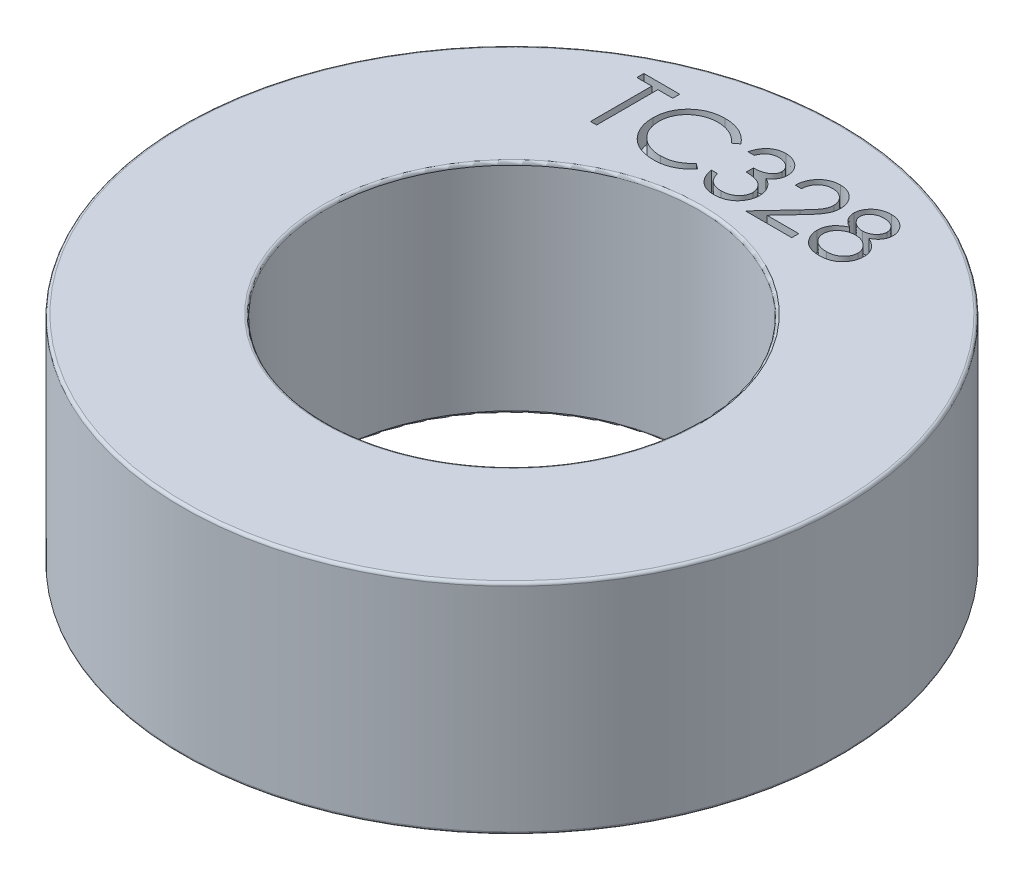
SolidWorks part; units mm, degrees
ref_plane "Front Plane" through (0, 0, 0) normal (0, 0, 1) x (1, 0, 0)
ref_plane "Top Plane" through (0, 0, 0) normal (0, 1, 0) x (1, 0, 0)
ref_plane "Right Plane" through (0, 0, 0) normal (1, 0, 0) x (0, 0, -1)
sketch "Toroidal Core TC328" plane through (0, 0, 0) normal (0, 0, 1) x (1, 0, 0)
  line L0 (0, -8.108) -> (0, 13.3131) construction
  line L2 (9.6961, 0) -> (16.7539, 0)
  line L3 (9.55, 0.1461) -> (9.55, 11.0539)
  line L4 (9.6961, 11.2) -> (16.7539, 11.2)
  line L5 (16.9, 0.1461) -> (16.9, 11.0539)
  arc A0 (9.6961, 0) -> (9.55, 0.1461) centre (9.6961, 0.1461) cw
  arc A1 (16.7539, 0) -> (16.9, 0.1461) centre (16.7539, 0.1461) ccw
  arc A2 (16.7539, 11.2) -> (16.9, 11.0539) centre (16.7539, 11.0539) cw
  arc A3 (9.55, 11.0539) -> (9.6961, 11.2) centre (9.6961, 11.0539) cw
  point P9 (9.55, 0)
  point P12 (16.9, 0)
  point P15 (16.9, 11.2)
  point P18 (9.55, 11.2)
  dimension "D4" = 0.1461
  dimension "D1" = 7.35
  dimension "D2" = 11.2
  dimension "D3" = 9.55
revolve "Revolve2" add sketch "Toroidal Core TC328" angle 360 about L0
sketch "Sketch1" plane through (0, 11.2, 0) normal (0, 1, 0) x (1, 0, 0)
  text T0 "TC328\r\n"
extrude "Cut-Extrude1" cut sketch "Sketch1" against normal blind 1
